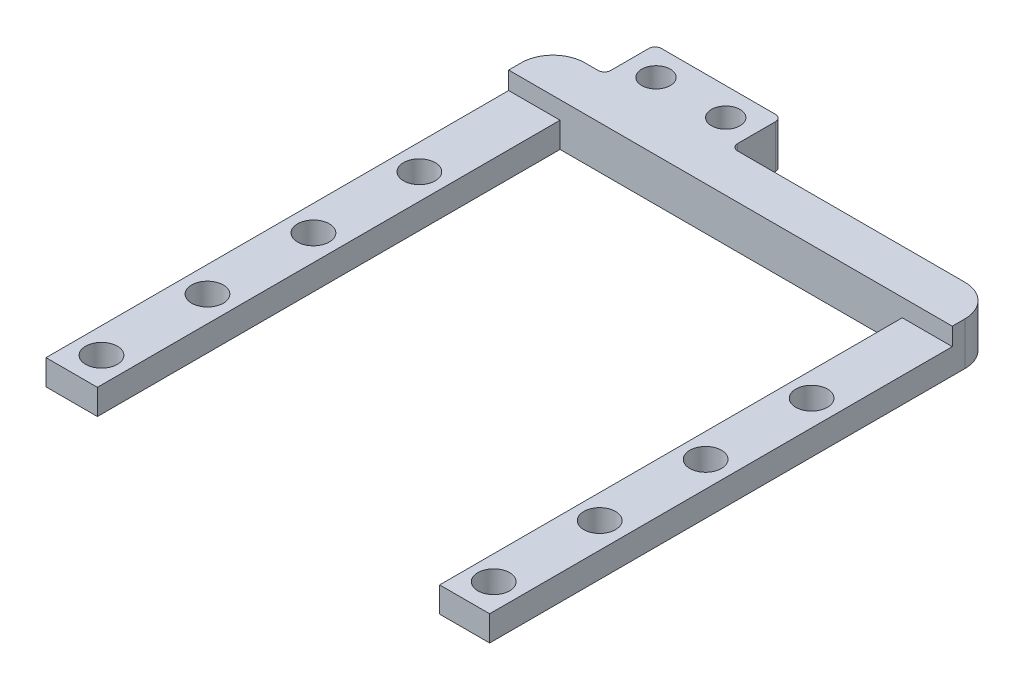
SolidWorks part; units mm, degrees
ref_plane "Front Plane" through (0, 0, 0) normal (0, 0, 1) x (1, 0, 0)
ref_plane "Top Plane" through (0, 0, 0) normal (0, 1, 0) x (1, 0, 0)
ref_plane "Right Plane" through (0, 0, 0) normal (1, 0, 0) x (0, 0, -1)
sketch "Sketch1" plane through (0, 0, 0) normal (0, 1, 0) x (1, 0, 0)
  line L1 (0, 0) -> (70, 0)
  line L2 (0, 0) -> (0, -80)
  line L3 (0, -80) -> (70, -80)
  line L4 (70, 0) -> (70, -80)
  dimension "D1" = 70
  dimension "D2" = 80
extrude "Boss-Extrude1" add sketch "Sketch1" along normal blind 6.8 contours L2 L3 L4 L1
sketch "Sketch2" plane through (0, 6.8, 0) normal (0, 1, 0) x (1, 0, 0)
  line L0 (0, -80) -> (70, -80) construction
  line L1 (8.11, -80) -> (62.11, -80)
  line L2 (8.11, -80) -> (8.11, -7)
  line L3 (8.11, -7) -> (62.11, -7)
  line L4 (62.11, -80) -> (62.11, -7)
  dimension "D1" = 54
  dimension "D2" = 73
  dimension "D3" = 8.11
extrude "Cut-Extrude1" cut sketch "Sketch2" against normal through all
sketch "Sketch3" plane through (0, 6.8, 0) normal (0, 1, 0) x (1, 0, 0)
  line L0 (0, -80) -> (8.11, -80) construction
  circle A0 centre (4.055, -75.3) radius 2.5
  dimension "D1" = 5
  dimension "D2" = 4.7
  dimension "D3" = 4.055
extrude "Cut-Extrude2" cut sketch "Sketch3" against normal through all
pattern_linear "LPattern1" count 4 spacing 16.72 along (0, 0, -1) of "Cut-Extrude2"
ref_plane "Plane1" through (35, 0, 0) normal (1, 0, 0) x (0, 0, -1)
mirror "Mirror1" about plane through (35, 0, 0) normal (1, 0, 0) of "LPattern1", "Cut-Extrude2"
sketch "Sketch4" plane through (0, 6.8, 0) normal (0, 1, 0) x (1, 0, 0)
  line L0 (0, 0) -> (70, 0) construction
  line L1 (8.11, 0) -> (28.11, 0)
  line L2 (8.11, 0) -> (8.11, 8)
  line L3 (8.11, 8) -> (28.11, 8)
  line L4 (28.11, 0) -> (28.11, 8)
  dimension "D1" = 8
  dimension "D2" = 20
sketch "Sketch5" plane through (0, 6.8, 0) normal (0, 1, 0) x (1, 0, 0)
  line L1 (0, -80) -> (8.11, -80)
  line L2 (0, -80) -> (0, -7)
  line L3 (0, -7) -> (8.11, -7)
  line L4 (8.11, -80) -> (8.11, -7)
extrude "Cut-Extrude3" cut sketch "Sketch5" against normal blind 2.8
mirror "Mirror2" about plane through (35, 0, 0) normal (1, 0, 0) of "Cut-Extrude3"
extrude "Boss-Extrude2" add sketch "Sketch4" against normal blind 6.8 contours L2 L3 L4 L1
sketch "Sketch7" plane through (0, 6.8, 0) normal (0, 1, 0) x (1, 0, 0)
  line L0 (28.11, 0) -> (28.11, 8) construction
  circle A0 centre (12.6256, 3.6256) radius 2.25
  circle A1 centre (23.6256, 3.6256) radius 2.25
  point P4 (28.11, 4)
  dimension "D1" = 4.5
  dimension "D2" = 4.5
  dimension "D3" = 11
  dimension "D4" = 4.5
extrude "Cut-Extrude4" cut sketch "Sketch7" against normal blind 6.8
fillet "Fillet1" radius 1 1 edges
fillet "Fillet2" radius 1 3 edges at (8.11, 3.4, -8) (28.11, 3.4, -8)
fillet "Fillet3" radius 5 2 edges at (0, 3.4, 0) (70, 3.4, 0)
